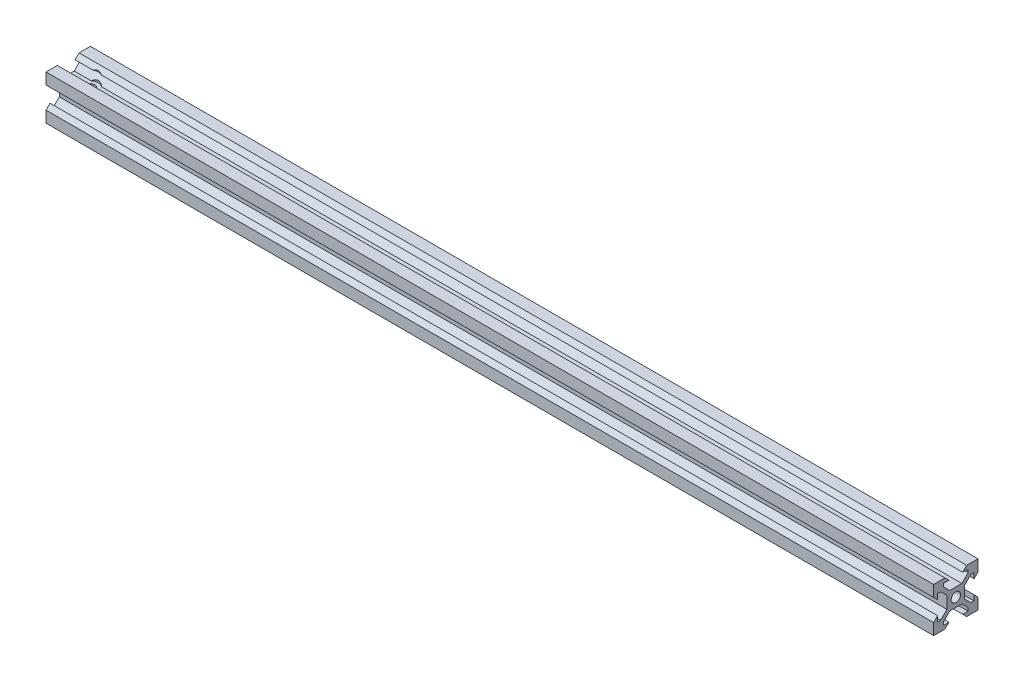
SolidWorks part; units mm, degrees
ref_plane "Front Plane" through (0, 0, 0) normal (0, 0, 1) x (1, 0, 0)
ref_plane "Top Plane" through (0, 0, 0) normal (0, 1, 0) x (1, 0, 0)
ref_plane "Right Plane" through (0, 0, 0) normal (1, 0, 0) x (0, 0, -1)
sketch "Sketch1" plane through (0, 0, 0) normal (1, 0, 0) x (0, 0, -1)
  line L0 (0, 0) -> (0, 20) construction
  line L1 (10, 14) -> (10, 6) construction
  line L2 (5.1, 20) -> (5.1, 0) construction
  line L3 (6.9, 18.2) -> (6.9, 1.8) construction
  line L4 (4.4444, 18.2) -> (4.4444, 1.8) construction
  line L5 (3.1716, 15.5556) -> (3.1716, 4.4444) construction
  line L6 (10, 6) -> (10, 14) construction
  line L7 (6, 12.7272) -> (6, 7.2728)
  line L8 (6, 7.2728) -> (3.1716, 4.4444)
  line L9 (1.8, 4.4444) -> (3.1716, 4.4444)
  line L10 (1.8, 4.4444) -> (1.8, 6.9)
  line L11 (1.8, 6.9) -> (0, 5.1)
  line L12 (0, 5.1) -> (0, 0)
  line L13 (0, 0) -> (5.1, 0)
  line L14 (5.1, 0) -> (6.9, 1.8)
  line L15 (6.9, 1.8) -> (4.4444, 1.8)
  line L16 (4.4444, 3.1716) -> (4.4444, 1.8)
  line L17 (4.4444, 3.1716) -> (7.2728, 6)
  line L18 (7.2728, 6) -> (12.7272, 6)
  line L19 (1.8, 15.5556) -> (1.8, 4.4444) construction
  line L20 (20, 10) -> (0, 10) construction
  line L21 (1.8, 10) -> (0, 10) construction
  line L22 (7.2728, 14) -> (7.2728, 6) construction
  line L23 (6.9, 1.8) -> (0, 1.8) construction
  line L24 (5.8586, 15.4142) -> (5.8586, 4.5858) construction
  line L25 (4.5858, 14.1414) -> (4.5858, 5.8586) construction
  line L26 (10, 10) -> (20, 20) construction
  line L27 (14.1414, 15.4142) -> (15.4142, 14.1414) construction
  line L28 (10, 10) -> (0, 0) construction
  line L29 (14.7778, 14.7778) -> (20, 20) construction
  line L30 (5.8586, 4.5858) -> (4.5858, 5.8586) construction
  line L31 (5.2222, 5.2222) -> (0, 0) construction
  line L32 (14.7778, 5.2222) -> (20, 0) construction
  line L33 (10, 6) -> (10, 14) construction
  line L34 (14.1414, 4.5858) -> (15.4142, 5.8586) construction
  line L35 (10, 10) -> (20, 0) construction
  line L36 (15.4142, 14.1414) -> (15.4142, 5.8586) construction
  line L37 (14.1414, 15.4142) -> (14.1414, 4.5858) construction
  line L38 (13.1, 1.8) -> (20, 1.8) construction
  line L39 (12.7272, 14) -> (12.7272, 6) construction
  line L40 (18.2, 10) -> (20, 10) construction
  line L41 (18.2, 15.5556) -> (18.2, 4.4444) construction
  line L42 (16.8284, 15.5556) -> (16.8284, 4.4444) construction
  line L43 (15.5556, 18.2) -> (15.5556, 1.8) construction
  line L44 (13.1, 18.2) -> (13.1, 1.8) construction
  line L45 (14.9, 20) -> (14.9, 0) construction
  line L46 (20, 0) -> (20, 20) construction
  line L47 (14, 12.7272) -> (16.8284, 15.5556)
  line L48 (18.2, 15.5556) -> (16.8284, 15.5556)
  line L49 (18.2, 15.5556) -> (18.2, 13.1)
  line L50 (18.2, 13.1) -> (20, 14.9)
  line L51 (20, 14.9) -> (20, 20)
  line L52 (20, 20) -> (14.9, 20)
  line L53 (14.9, 20) -> (13.1, 18.2)
  line L54 (13.1, 18.2) -> (15.5556, 18.2)
  line L55 (15.5556, 16.8284) -> (15.5556, 18.2)
  line L56 (15.5556, 16.8284) -> (12.7272, 14)
  line L57 (15.5556, 3.1716) -> (12.7272, 6)
  line L58 (15.5556, 3.1716) -> (15.5556, 1.8)
  line L59 (13.1, 1.8) -> (15.5556, 1.8)
  line L60 (14.9, 0) -> (13.1, 1.8)
  line L61 (20, 0) -> (14.9, 0)
  line L62 (20, 5.1) -> (20, 0)
  line L63 (5.2222, 14.7778) -> (0, 20) construction
  line L64 (5.8586, 15.4142) -> (4.5858, 14.1414) construction
  line L65 (18.2, 6.9) -> (20, 5.1)
  line L66 (10, 10) -> (0, 20) construction
  line L67 (18.2, 4.4444) -> (18.2, 6.9)
  line L68 (18.2, 4.4444) -> (16.8284, 4.4444)
  line L69 (14, 7.2728) -> (16.8284, 4.4444)
  line L70 (14, 12.7272) -> (14, 7.2728)
  line L93 (7.2728, 14) -> (12.7272, 14)
  line L94 (4.4444, 16.8284) -> (7.2728, 14)
  line L95 (4.4444, 16.8284) -> (4.4444, 18.2)
  line L96 (6.9, 18.2) -> (4.4444, 18.2)
  line L97 (5.1, 20) -> (6.9, 18.2)
  line L98 (0, 20) -> (5.1, 20)
  line L99 (0, 14.9) -> (0, 20)
  line L100 (1.8, 13.1) -> (0, 14.9)
  line L101 (1.8, 15.5556) -> (1.8, 13.1)
  line L102 (1.8, 15.5556) -> (3.1716, 15.5556)
  line L103 (6, 12.7272) -> (3.1716, 15.5556)
  circle A0 centre (10, 10) radius 2.1
  point P57 (14, 10)
  point P108 (6, 10)
  dimension "D5" = 4.2
  dimension "D2" = 20
  dimension "D3" = 10
  dimension "D4" = 5.1
  dimension "D6" = 10
  dimension "D7" = 1.8
  dimension "D8" = 1.8
  dimension "D9" = 1.3716
  dimension "D10" = 1.8
  dimension "D11" = 1.8
  dimension "D12" = 4
  dimension "D13" = 1.2728
  dimension "D14" = 5.1
  dimension "D16" = 1.8
  dimension "D18" = 4
extrude "Boss-Extrude1" add sketch "Sketch1" along normal blind 400
sketch "Sketch2" plane through (0, 6, 0) normal (0, -1, 0) x (1, 0, 0)
  line L0 (400, -20) -> (0, -20) construction
  line L1 (0, 0) -> (0, -5.1) construction
  circle A0 centre (10, -10) radius 2
  dimension "D1" = 10
  dimension "D2" = 10
  dimension "D3" = 4
extrude "Cut-Extrude1" cut sketch "Sketch2" against normal blind 10
sketch "Sketch3" plane through (0, 14, 0) normal (0, 1, 0) x (1, 0, 0)
  line L1 (0, 12.7272) -> (0, 7.2728) construction
  line L2 (400, 20) -> (0, 20) construction
  circle A0 centre (10, 10) radius 3.6
  dimension "D1" = 7.2
  dimension "D2" = 10
  dimension "D3" = 10
extrude "Cut-Extrude2" cut sketch "Sketch3" along normal blind 13
